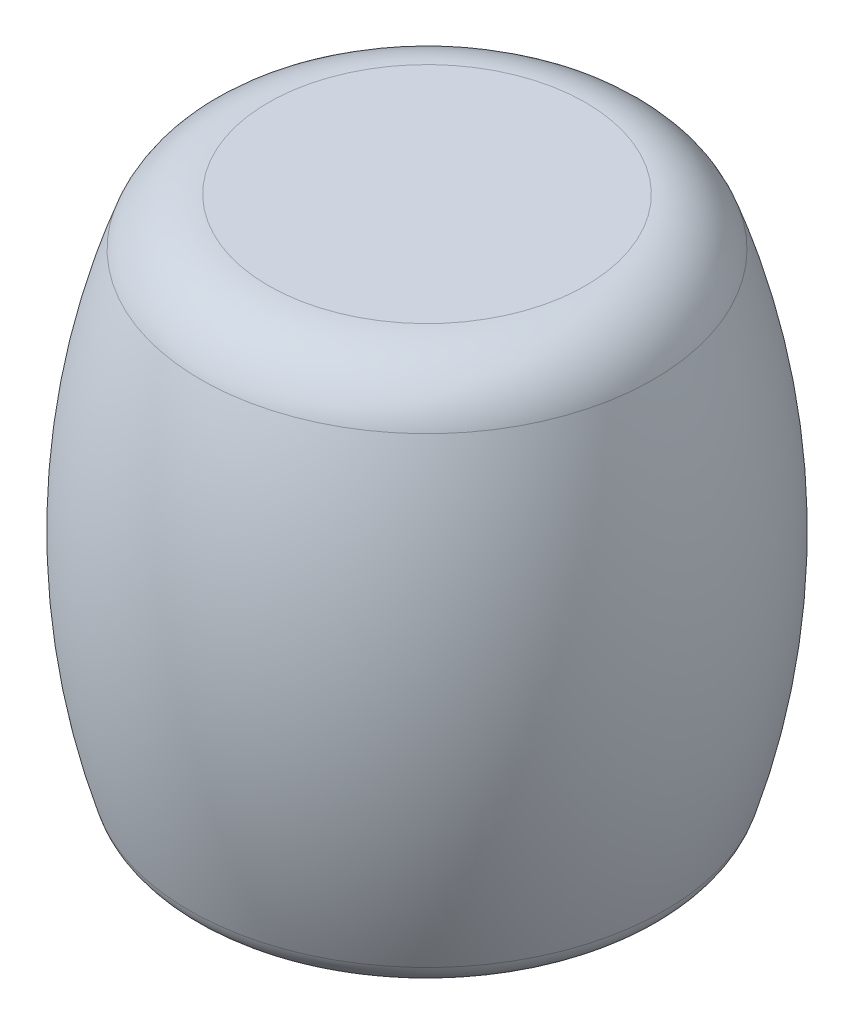
SolidWorks part; units mm, degrees
ref_plane "Front Plane" through (0, 0, 0) normal (0, 0, 1) x (1, 0, 0)
ref_plane "Top Plane" through (0, 0, 0) normal (0, 1, 0) x (1, 0, 0)
ref_plane "Right Plane" through (0, 0, 0) normal (1, 0, 0) x (0, 0, -1)
sketch "Sketch2" plane through (0, 0, 0) normal (0, 0, 1) x (1, 0, 0)
  line L0 (0, 300) -> (0, -290) construction
  line L1 (-142.8245, 0) -> (143.6743, 0) construction
  line L2 (-254.2692, 98.4782) -> (313.289, 98.4782) construction
  line L3 (0, -20) -> (-90, -20) construction
  line L4 (-90, -83.4454) -> (-90, 295.8002) construction
  line L8 (-23.8094, 220) -> (-90, 220)
  line L9 (-23.8094, 205) -> (-90, 205)
  line L10 (-90, 220) -> (-90, 205)
  line L11 (-3.7257, 0) -> (-12.4988, 0)
  line L12 (-12.4988, 0) -> (-12.4988, 14.2371)
  line L13 (-12.4988, 14.2371) -> (-5.3515, 14.9116)
  arc A0 (8.9892, 10.5134) -> (4.4145, 200.1691) centre (-277.8247, 98.4782) ccw
  arc A2 (8.9892, 10.5134) -> (-3.7257, 0) centre (-5.3515, 14.9116) cw
  arc A10 (-5.3515, 14.9116) -> (-5.3515, 14.9116) centre (-5.3515, 14.9116) cw
  arc A11 (-5.3515, 14.9116) -> (-9.6974, 195.0845) centre (-277.8247, 98.4782) ccw
  arc A12 (-23.8094, 205) -> (-9.6974, 195.0845) centre (-23.8094, 190) cw
  arc A18 (-23.8094, 220) -> (4.4145, 200.1691) centre (-23.8094, 190) cw
  point P11 (-86.4792, 156.5384)
  point P13 (-4.944, -0.0828)
  point P14 (0, 0)
  point P30 (-6.5748, 7.2962)
  point P31 (-86.4792, 156.5384)
  point P32 (-89.8547, -12.7145)
  dimension "D3" = 300
  dimension "D6" = 15
  dimension "D7" = 15
  dimension "D1" = 30
  dimension "D4" = 220
  dimension "D2" = 90
  dimension "D5" = 20
revolve "Revolve1" add sketch "Sketch2" angle 360 about L4
sketch "Sketch3" plane through (0, 0, 0) normal (0, -1, 0) x (1, 0, 0)
  circle A0 centre (-90, 0) radius 77.5012
  circle A1 centre (-90, 0) radius 81
  dimension "D1" = 155.0025
  dimension "D2" = 162
extrude "Cut-Extrude1" cut sketch "Sketch3" against normal blind 20
